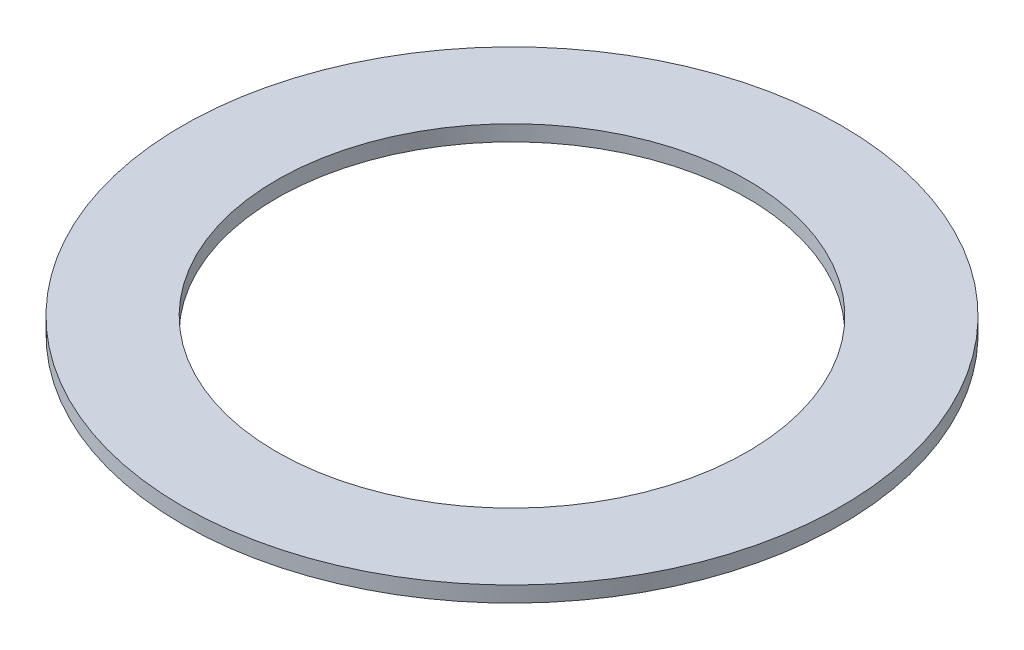
SolidWorks part; units mm, degrees
material "Cast Carbon Steel"
ref_plane "Front" through (0, 0, 0) normal (0, 0, 1) x (1, 0, 0)
ref_plane "Top" through (0, 0, 0) normal (0, 1, 0) x (1, 0, 0)
ref_plane "Right" through (0, 0, 0) normal (1, 0, 0) x (0, 0, -1)
sketch "Sketch1" plane through (0, 0, 0) normal (0, 1, 0) x (1, 0, 0)
  circle A0 centre (0, 0) radius 7.5
  circle A1 centre (0, 0) radius 10.5
extrude "Boss-Extrude1" add sketch "Sketch1" along normal blind 0.5
